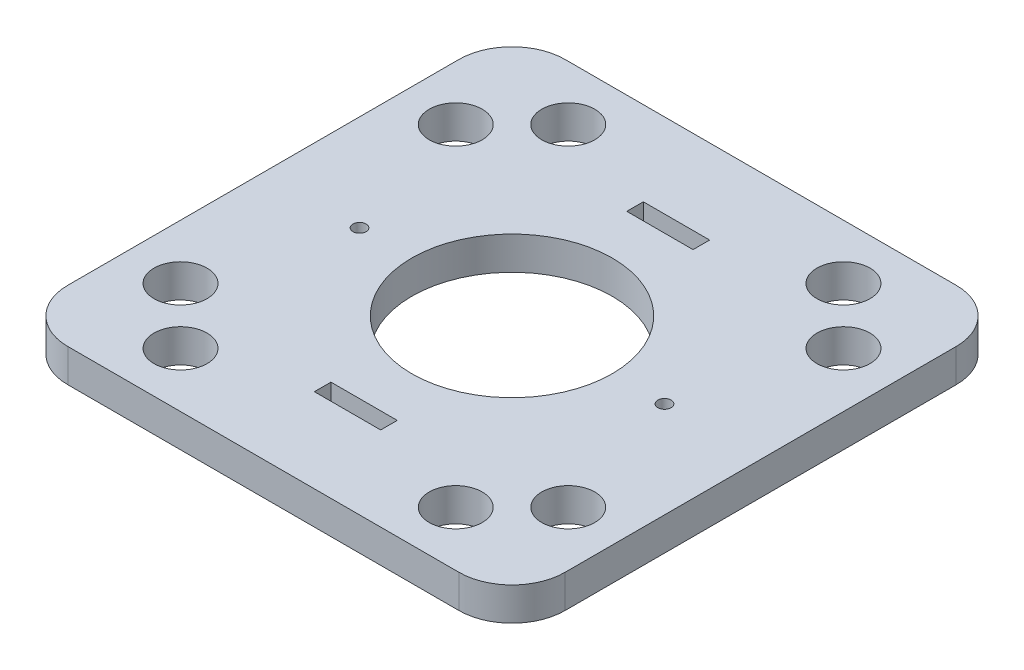
SolidWorks part; units mm, degrees
ref_plane "Front Plane" through (0, 0, 0) normal (0, 0, 1) x (1, 0, 0)
ref_plane "Top Plane" through (0, 0, 0) normal (0, 1, 0) x (1, 0, 0)
ref_plane "Right Plane" through (0, 0, 0) normal (1, 0, 0) x (0, 0, -1)
sketch "Sketch2" plane through (0, 0, 0) normal (0, 1, 0) x (1, 0, 0)
  line L0 (0, 0) -> (37.5, 0) construction
  line L1 (-37.5, -37.5) -> (37.5, -37.5)
  line L2 (-37.5, -37.5) -> (-37.5, 37.5)
  line L3 (-37.5, 37.5) -> (37.5, 37.5)
  line L4 (37.5, -37.5) -> (37.5, 37.5)
  line L5 (-37.5, -37.5) -> (37.5, 37.5) construction
  line L6 (-37.5, 37.5) -> (37.5, -37.5) construction
  line L7 (-25, -25) -> (25, -25) construction
  line L8 (-25, -25) -> (-25, 25) construction
  line L9 (-25, 25) -> (25, 25) construction
  line L10 (25, -25) -> (25, 25) construction
  line L11 (-25, -25) -> (25, 25) construction
  line L12 (-25, 25) -> (25, -25) construction
  line L13 (0, 0) -> (0, 37.5) construction
  line L14 (0, 0) -> (-23, 0) construction
  line L15 (5, -24.81) -> (5, -22.31)
  line L16 (-5, 24.81) -> (5, 24.81)
  line L17 (-5, 24.81) -> (-5, 22.31)
  line L18 (-5, 22.31) -> (5, 22.31)
  line L19 (5, 24.81) -> (5, 22.31)
  line L20 (-5, 24.81) -> (5, 22.31) construction
  line L21 (-5, 22.31) -> (5, 24.81) construction
  line L22 (-5, -22.31) -> (5, -22.31)
  line L23 (-5, -24.81) -> (-5, -22.31)
  line L24 (-5, -24.81) -> (5, -24.81)
  line L25 (20.7574, 29.2426) -> (29.2426, 20.7574) construction
  circle A0 centre (0, 0) radius 15.1197
  circle A5 centre (-23, 0) radius 1
  circle A6 centre (23, 0) radius 1
  circle A7 centre (29.2426, 20.7574) radius 4
  circle A8 centre (20.7574, 29.2426) radius 4
  circle A9 centre (-20.7574, -29.2426) radius 4
  circle A10 centre (-29.2426, -20.7574) radius 4
  circle A11 centre (-20.7574, 29.2426) radius 4
  circle A12 centre (-29.2426, 20.7574) radius 4
  circle A13 centre (29.2426, -20.7574) radius 4
  circle A14 centre (20.7574, -29.2426) radius 4
  point P0 (0, 0)
  point P6 (0, 0)
  point P18 (25, 25)
  point P23 (0, 23.56)
  dimension "D1" = 75
  dimension "D2" = 50
extrude "Boss-Extrude2" add sketch "Sketch2" along normal blind 5
fillet "Fillet1" radius 8 4 edges at (-37.5, 2.5, 37.5) (-37.5, 2.5, -37.5) (37.5, 2.5, 37.5) (37.5, 2.5, -37.5)
